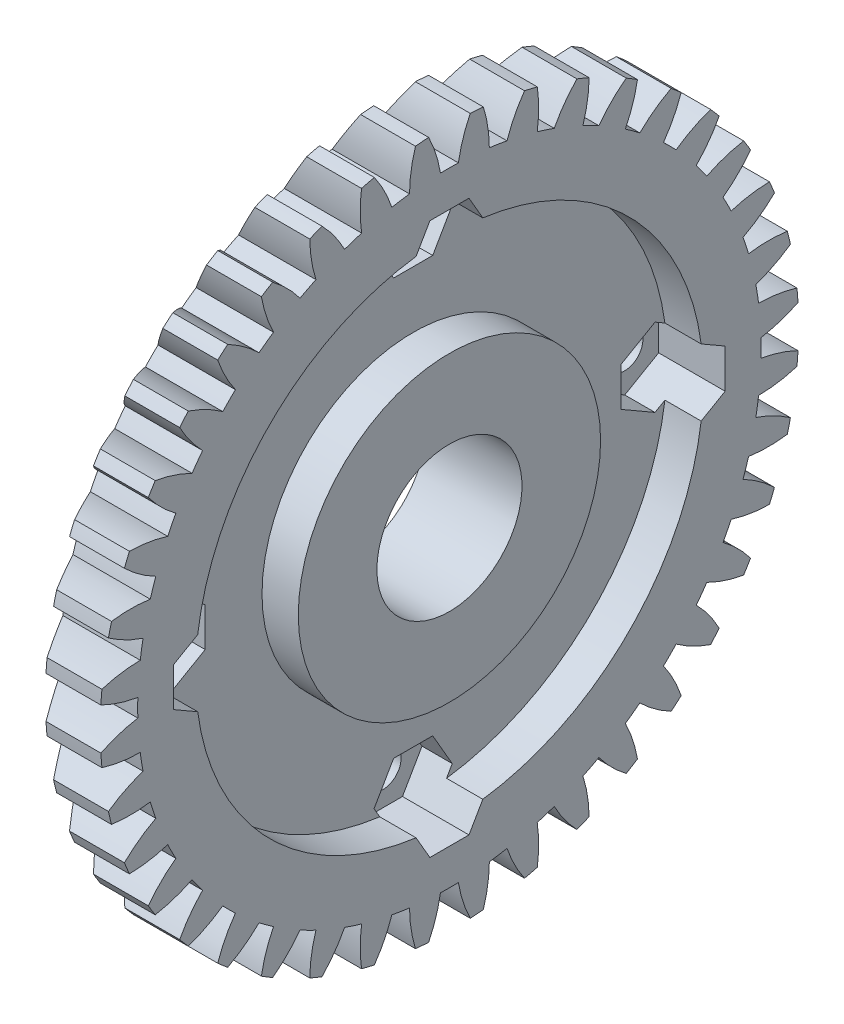
SolidWorks part; units mm, degrees
ref_plane "Plane1" through (0, 0, 0) normal (0, 0, 1) x (1, 0, 0)
ref_plane "Plane2" through (0, 0, 0) normal (0, 1, 0) x (1, 0, 0)
ref_plane "Plane3" through (0, 0, 0) normal (1, 0, 0) x (0, 0, -1)
sketch "HoldingSke" plane through (0, 0, 0) normal (0, 1, 0) x (1, 0, 0)
  line L0 (0, 0) -> (0.5571, -0.4675)
  line L1 (-15, 0) -> (100, 0) construction
  line L2 (0, 0) -> (-2.1039, 2.3779)
  line L3 (0, 0) -> (-11.863, 4.5341)
  line L4 (0, 0) -> (6.6156, 5.5511)
  line L5 (0, 0) -> (-46.8476, -17.4728)
  line L6 (0, 0) -> (-6.6317, -4.4744)
  line L7 (-2.1039, 2.3779) -> (8.6586, 51.2059)
  line L8 (-76.2, 54.61) -> (-73.4, 54.61)
  line L9 (-67.7845, 28.3722) -> (-49.3413, 33.142)
  line L10 (-76.2, 71.12) -> (104.1128, 71.12)
  line L11 (0, 0) -> (-8, 0)
  line L12 (-76.2, 101.6) -> (-76.151, 101.6)
  line L13 (24.9733, 27.94) -> (52.9518, 28.4284)
  line L14 (24.9733, 27.94) -> (24.9743, 27.94)
  line L15 (24.9733, 27.94) -> (100.4006, 29.5858)
  line L16 (-63.627, -1.375) -> (-12.827, -1.375)
  circle A0 centre (0, 0) radius 6
  circle A1 centre (0, 0) radius 25.7803
  circle A2 centre (0, 0) radius 37.5
  circle A3 centre (0, 0) radius 6
  dimension "MHD" = 51.5605
  dimension "Hub_dia" = 75
  dimension "Bore" = 12
  dimension "MBD" = 12
  dimension "Num_teeth" = 40
  dimension "Pitch" = 0.7273
  dimension "Overall_len" = 50
  dimension "Show_teeth" = 40
  dimension "Thickness" = 8
  dimension "OAL" = 50.0001
  dimension "T_dim" = 2.8
  dimension "Ap" = 14.5
  dimension "H" = 19.05
  dimension "Pitch_radius" = 180.3128
  dimension "Width" = 8
  dimension "Backlash" = 0.049
  dimension "Addendum_fac" = 1
  dimension "Dedendum_fac" = 1.25
  dimension "Clearance_fac" = 0.25
  dimension "Dedendum_add" = 0.001
  dimension "Module" = 1.375
sketch "BasProSke" plane through (0, 0, 0) normal (0, 1, 0) x (1, 0, 0)
  line L0 (-10, 0) -> (60, 0) construction
  line L1 (0, 0) -> (0, 28.875)
  line L2 (0, 0) -> (8, 0)
  line L3 (8, 0) -> (8, 28.875)
  line L4 (8, 28.875) -> (0, 28.875)
  dimension "Thickness" = 8
  dimension "Diameter" = 57.75
revolve "Base-Revolve" add sketch "BasProSke" angle 360 about L0
sketch "TooCutSke" plane through (0, 0, 0) normal (1, 0, 0) x (0, 0, -1)
  line L1 (0, 0) -> (0, 107) construction
  line L2 (0, 0) -> (-1.1654, 27.4753) construction
  line L3 (0, 0) -> (-4.3124, 54.7946) construction
  line L4 (-1.1654, 27.4753) -> (-2.1562, 27.3973) construction
  arc A0 (0.7399, 25.7696) -> (-0.7399, 25.7696) centre (0, 0) ccw
  arc A1 (1.7331, 28.8484) -> (-1.7331, 28.8484) centre (0, 0) ccw
  circle A2 centre (0, 0) radius 27.5 construction
  circle A3 centre (0, 0) radius 26.6241 construction
  arc A4 (-0.7399, 25.7696) -> (-1.7331, 28.8484) centre (-11.5914, 23.9683) ccw
  arc A5 (1.7331, 28.8484) -> (0.7399, 25.7696) centre (11.5914, 23.9683) ccw
  dimension "Root_dia" = 51.5605
  dimension "Overcut_dia" = 57.8008
  dimension "Pitch_dia" = 55
  dimension "Base_dia" = 53.2481
  dimension "Flank_rad" = 11
  dimension "Half_ang" = 4.5
  dimension "Half_CT" = 0.9939
extrude "ToothCut" cut sketch "TooCutSke" along normal through all
fillet "Breaks" [suppressed] radius 0.0275
fillet "RootFillets" [suppressed] radius 0.3448
pattern_circular "TeethCuts" count 40 over 360 about axis through (0, 0, 0) along (1, 0, 0) of "ToothCut", "RootFillets", "Breaks"
sketch "HubNeaOneSke" plane through (0, 0, 0) normal (-1, 0, 0) x (0, 0, 1)
  circle A0 centre (0, 0) radius 25.7803
  dimension "Diameter" = 51.5605
extrude "HubNearOne" [suppressed] add sketch "HubNeaOneSke" along normal blind 42.0001
sketch "HubNeaBotSke" plane through (0, 0, 0) normal (-1, 0, 0) x (0, 0, 1)
  circle A0 centre (0, 0) radius 25.7803
  dimension "Diameter" = 51.5605
extrude "HubNearBoth" [suppressed] add sketch "HubNeaBotSke" along normal blind 21
ref_plane "FarPln" through (8, 0, 0) normal (1, 0, 0) x (0, 0, -1)
sketch "HubFarSke" plane through (8, 0, 0) normal (1, 0, 0) x (0, 0, -1)
  circle A0 centre (0, 0) radius 25.7803
  dimension "Diameter" = 51.5605
extrude "HubFar" [suppressed] add sketch "HubFarSke" along normal blind 21
sketch "BorSke" plane through (0, 0, 0) normal (1, 0, 0) x (0, 0, -1)
  circle A0 centre (0, 0) radius 6
  dimension "Diameter" = 12
extrude "Bore" cut sketch "BorSke" along normal mid plane 100.0001
sketch "KeySke" plane through (0, 0, 0) normal (1, 0, 0) x (0, 0, -1)
  line L0 (-3, 0) -> (-3, 8.8)
  line L1 (-3, 8.8) -> (3, 8.8)
  line L2 (3, 8.8) -> (3, 0)
  line L3 (0, 0) -> (0, 34) construction
  line L4 (-3, 0) -> (3, 0)
  dimension "Offset" = 8.8
  dimension "Width" = 6
extrude "Keyway" [suppressed] cut sketch "KeySke" along normal mid plane 100.0001
pattern_circular "Keyway2" [suppressed] count 2 every 90 about axis through (-10, 0, 0) along (1, 0, 0)
sketch "草图1" plane through (8, 0, 0) normal (1, 0, 0) x (0, 0, -1)
  line L5 (0, 0) -> (11.8721, 0) construction
  circle A0 centre (0, 0) radius 6 construction
  circle A1 centre (0, 0) radius 6
  circle A4 centre (20, 0) radius 1.5
  circle A6 centre (0, 0) radius 20
  circle A7 centre (0, -20) radius 1.5
  circle A8 centre (-20, 0) radius 1.5
  circle A9 centre (0, 20) radius 1.5
  point P10 (20, 0)
  point P18 (0, 0)
  dimension "D3" = 4
  dimension "D4" = 40
  dimension "D2" = 3
extrude "切除-拉伸1" cut sketch "草图1" against normal through all
sketch "草图2" plane through (8, 0, 0) normal (1, 0, 0) x (0, 0, -1)
  line L43 (-1.6166, 17.2) -> (1.6166, 17.2)
  line L44 (1.6166, 17.2) -> (3.2332, 20)
  line L45 (3.2332, 20) -> (1.6166, 22.8)
  line L46 (1.6166, 22.8) -> (-1.6166, 22.8)
  line L47 (-1.6166, 22.8) -> (-3.2332, 20)
  line L48 (-3.2332, 20) -> (-1.6166, 17.2)
  line L66 (17.2, 1.6166) -> (17.2, -1.6166)
  line L67 (17.2, -1.6166) -> (20, -3.2332)
  line L68 (20, -3.2332) -> (22.8, -1.6166)
  line L69 (22.8, -1.6166) -> (22.8, 1.6166)
  line L70 (22.8, 1.6166) -> (20, 3.2332)
  line L71 (20, 3.2332) -> (17.2, 1.6166)
  line L72 (1.6166, -17.2) -> (-1.6166, -17.2)
  line L73 (-1.6166, -17.2) -> (-3.2332, -20)
  line L74 (-3.2332, -20) -> (-1.6166, -22.8)
  line L75 (-1.6166, -22.8) -> (1.6166, -22.8)
  line L76 (1.6166, -22.8) -> (3.2332, -20)
  line L77 (3.2332, -20) -> (1.6166, -17.2)
  line L78 (-17.2, -1.6166) -> (-17.2, 1.6166)
  line L79 (-17.2, 1.6166) -> (-20, 3.2332)
  line L80 (-20, 3.2332) -> (-22.8, 1.6166)
  line L81 (-22.8, 1.6166) -> (-22.8, -1.6166)
  line L82 (-22.8, -1.6166) -> (-20, -3.2332)
  line L83 (-20, -3.2332) -> (-17.2, -1.6166)
  circle A2 centre (0, 0) radius 6 construction
  circle A4 centre (20, 0) radius 1.5 construction
  circle A7 centre (0, 0) radius 6
  circle A9 centre (20, 0) radius 1.5
  circle A10 centre (0, 0) radius 12.5
  circle A15 centre (0, 20) radius 1.5 construction
  circle A16 centre (0, -20) radius 1.5 construction
  circle A17 centre (-20, 0) radius 1.5 construction
  circle A18 centre (-20, 0) radius 1.5
  circle A19 centre (0, -20) radius 1.5
  circle A20 centre (0, 20) radius 1.5
  point P43 (0, 0)
  dimension "D1" = 5.6
  dimension "D3" = 25
  dimension "D2" = 4
  dimension "D5" = 20
  dimension "D4" = 29.9579
extrude "切除-拉伸2" cut sketch "草图2" against normal blind 5.5
sketch "草图3" plane through (8, 0, 0) normal (1, 0, 0) x (0, 0, -1)
  line L0 (-1.6166, 22.8) -> (-3.2332, 20) construction
  line L1 (1.6166, 22.8) -> (-1.6166, 22.8) construction
  line L2 (3.2332, 20) -> (1.6166, 22.8) construction
  line L5 (-3.2332, 20) -> (-1.6166, 17.2) construction
  line L6 (-1.6166, 22.8) -> (-3.2332, 20)
  line L7 (1.6166, 22.8) -> (-1.6166, 22.8)
  line L8 (3.2332, 20) -> (1.6166, 22.8)
  line L11 (-3.2332, 20) -> (-1.6166, 17.2)
  circle A0 centre (0, 0) radius 6 construction
  circle A2 centre (0, 0) radius 6
  circle A4 centre (0, 0) radius 21
  circle A5 centre (0, 0) radius 12.5
  dimension "D1" = 25
  dimension "D2" = 42
extrude "切除-拉伸3" cut sketch "草图3" against normal blind 3
sketch3d "3D草图1"
  line L0 (0, 0, 0) -> (0, 0, 46.2328) construction
  line L1 (0, 0, 0) -> (0, 35.6089, 0) construction
  line L3 (0, 0, 0) -> (-37.0636, 0, 0) construction
sketch "草图7" plane through (0, 0, 0) normal (0, 1, 0) x (1, 0, 0)
  line L6 (0, -29.7688) -> (0, -23.1164)
  line L10 (0, 200000) -> (0, -200046.2328) construction
  line L11 (0, -23.1164) -> (4, -29.7688)
  line L12 (4, -29.7688) -> (0, -29.7688)
  dimension "D1" = 4
  dimension "D2" = 7.7624
revolve "切除-旋转4" cut sketch "草图7" angle 360 about L3
equation "' \"Module@HoldingSke\" = 6.35"
equation "' \"Num_teeth@HoldingSke\" = 12"
equation "' \"Ap@HoldingSke\" =  20"
equation "' \"Ap@HoldingSke\" = 20"
equation "' \"Width@HoldingSke\" = 0.5 * 25.4"
equation "' \"Hub_dia@HoldingSke\"= 1 * 25.4"
equation "' \"Hub_dia@HoldingSke\" = 1 * 25.4"
equation "' \"Overall_len@HoldingSke\" = 1.0 * 25.4"
equation "' \"Bore@HoldingSke\" = 0.75 * 25.4"
equation "' \"T_dim@HoldingSke\" = 0.1 * 25.4"
equation "' \"Width@KeySke\" = 0.25 * 25.4"
equation "' \"Show_teeth@HoldingSke\" = 13"
equation "' \"Backlash@HoldingSke\" = 0.009 * 25.4"
equation "' \"Addendum_fac@HoldingSke\" = 1.0"
equation "' \"Dedendum_fac@HoldingSke\" = 1.25"
equation "' \"Dedendum_add@HoldingSke\" = 0.00005 * 25.4"
equation "' \"Clearance_fac@HoldingSke\" = 0.25"
equation "\"Pitch@HoldingSke\" = 1 / \"Module@HoldingSke\""
equation "\"Overcut_dia@TooCutSke\" = (\"Num_teeth@HoldingSke\" + 2 * \"Addendum_fac@HoldingSke\") / \"Pitch@HoldingSke\" + 0.002 * 25.4"
equation "\"Pitch_dia@TooCutSke\" = \"Num_teeth@HoldingSke\" / \"Pitch@HoldingSke\""
equation "\"Base_dia@TooCutSke\" = \"Num_teeth@HoldingSke\" / \"Pitch@HoldingSke\" * cos((\"Ap@HoldingSke\"  * 3.14159265 / 180))"
equation "\"Root_dia@TooCutSke\" = (\"Num_teeth@HoldingSke\" + 2) / \"Pitch@HoldingSke\" - 2 * (\"Addendum_fac@HoldingSke\" + \"Dedendum_fac@HoldingSke\") / \"Pitch@HoldingSke\" - \"Dedendum_add@HoldingSke\" * 2"
equation "\"Half_ang@TooCutSke\" = 180 / \"Num_teeth@HoldingSke\""
equation "\"Half_CT@TooCutSke\" = \"Num_teeth@HoldingSke\" / \"Pitch@HoldingSke\" * sin((3.14159265 / 2 / \"Num_teeth@HoldingSke\")) / 2 - 7 * \"Backlash@HoldingSke\" / 4"
equation "\"Flank_rad@TooCutSke\" = \"Num_teeth@HoldingSke\" / \"Pitch@HoldingSke\" / 5"
equation "\"Radius@RootFillets\" = \"Clearance_fac@HoldingSke\" / \"Pitch@HoldingSke\" + \"Dedendum_add@HoldingSke\""
equation "\"Break_rad@Breaks\" = 0.02 / \"Pitch@HoldingSke\""
equation "\"Thickness@HoldingSke\" = \"Width@HoldingSke\""
equation "\"OAL@HoldingSke\" = \"Thickness@HoldingSke\""
equation "\"MHD@HoldingSke\" = (\"Num_teeth@HoldingSke\" + 2) / \"Pitch@HoldingSke\" - 2 * (\"Addendum_fac@HoldingSke\" + \"Dedendum_fac@HoldingSke\")  / \"Pitch@HoldingSke\" - \"Dedendum_add@HoldingSke\" * 2"
equation "\"MBD@HoldingSke\" = (\"Num_teeth@HoldingSke\" + 2) / \"Pitch@HoldingSke\" - 2 * (\"Addendum_fac@HoldingSke\" + \"Dedendum_fac@HoldingSke\")  / \"Pitch@HoldingSke\" - \"Dedendum_add@HoldingSke\" * 2 - 0.002 * 25.4"
equation "\"MHD@HoldingSke\" = ((sgn( \"MHD@HoldingSke\" - \"Hub_dia@HoldingSke\" )-1)*( \"MHD@HoldingSke\" - \"Hub_dia@HoldingSke\" ))/-2+ \"Hub_dia@HoldingSke\""
equation "\"MBD@HoldingSke\" = ((sgn( \"MBD@HoldingSke\" - \"Bore@HoldingSke\" )-1)*( \"MBD@HoldingSke\" - \"Bore@HoldingSke\" ))/-2+ \"Bore@HoldingSke\""
equation "\"OAL@HoldingSke\" = ((sgn( \"OAL@HoldingSke\" - \"Overall_len@HoldingSke\" )+1)*( \"OAL@HoldingSke\" - \"Overall_len@HoldingSke\" ))/2 + \"Overall_len@HoldingSke\" + 0.000002 * 25.4"
equation "\"Num_teeth@TeethCuts\" = int( \"Show_teeth@HoldingSke\" ) + 1"
equation "\"Num_teeth@TeethCuts\" = ((sgn( \"Num_teeth@TeethCuts\" - \"Num_teeth@HoldingSke\" )-1)*( \"Num_teeth@TeethCuts\" - \"Num_teeth@HoldingSke\" ))/-2+ \"Num_teeth@HoldingSke\""
equation "\"Num_teeth@TeethCuts\" = ((sgn( \"Num_teeth@TeethCuts\" - 2.0)+1)*( \"Num_teeth@TeethCuts\" - 2.0))/2 +2.0"
equation "\"Angle@TeethCuts\" = 360.0 / \"Num_teeth@HoldingSke\""
equation "\"Diameter@BasProSke\" = (\"Num_teeth@HoldingSke\" + 2 * \"Addendum_fac@HoldingSke\") / \"Pitch@HoldingSke\""
equation "\"Thickness@BasProSke\"  = \"Thickness@HoldingSke\""
equation "' \"Fillet_rad@BasProSke\" =  \"Thickness@HoldingSke\" * 0.05"
equation "' \"Fillet_rad@BasProSke\" = \"Thickness@HoldingSke\" * 0.05"
equation "\"MHD@HoldingSke\" = ((sgn( \"MHD@HoldingSke\" - \"Root_dia@TooCutSke\" )-1)*( \"MHD@HoldingSke\" - \"Root_dia@TooCutSke\" ))/-2+ \"Root_dia@TooCutSke\""
equation "\"Diameter@HubNeaOneSke\" = \"MHD@HoldingSke\""
equation "\"Length@HubNearOne\" = \"OAL@HoldingSke\" - \"Thickness@BasProSke\""
equation "\"Diameter@HubNeaBotSke\" = \"MHD@HoldingSke\""
equation "\"Length@HubNearBoth\" = ( \"OAL@HoldingSke\" - \"Thickness@BasProSke\" ) / 2.0"
equation "\"Thickness@FarPln\" = \"Thickness@BasProSke\""
equation "\"Diameter@HubFarSke\" = \"MHD@HoldingSke\""
equation "\"Length@HubFar\" = ( \"OAL@HoldingSke\" - \"Thickness@BasProSke\" ) / 2.0"
equation "\"Diameter@BorSke\" = \"MBD@HoldingSke\""
equation "\"D1@Bore\" = \"OAL@HoldingSke\" * 2.0"
equation "\"D1@Keyway\" = \"OAL@HoldingSke\" * 2.0"
equation "\"Offset@KeySke\" = \"T_dim@HoldingSke\" + \"MBD@HoldingSke\" / 2.0"
